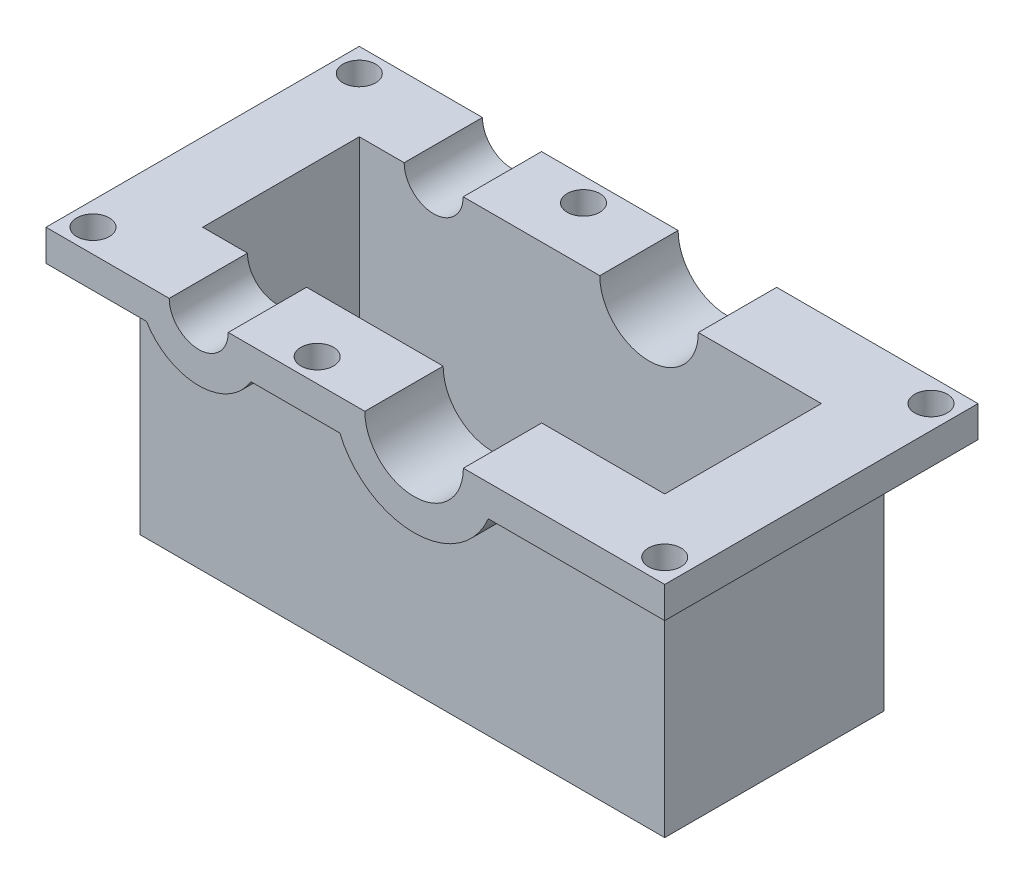
SolidWorks part; units mm, degrees
ref_plane "Front Plane" through (0, 0, 0) normal (0, 0, 1) x (1, 0, 0)
ref_plane "Top Plane" through (0, 0, 0) normal (0, 1, 0) x (1, 0, 0)
ref_plane "Right Plane" through (0, 0, 0) normal (1, 0, 0) x (0, 0, -1)
sketch "Sketch1" plane through (0, 0, 0) normal (0, 1, 0) x (1, 0, 0)
  line L1 (-21.2725, 8.89) -> (21.2725, 8.89)
  line L2 (-21.2725, 8.89) -> (-21.2725, -8.89)
  line L3 (-21.2725, -8.89) -> (21.2725, -8.89)
  line L4 (21.2725, 8.89) -> (21.2725, -8.89)
  line L5 (-21.2725, 8.89) -> (21.2725, -8.89) construction
  line L6 (-21.2725, -8.89) -> (21.2725, 8.89) construction
  point P0 (0, 0)
  dimension "D1" = 17.78
  dimension "D2" = 42.545
extrude "Boss-Extrude1" add sketch "Sketch1" along normal blind 2.54
sketch "Sketch2" plane through (0, 2.54, 0) normal (0, 1, 0) x (1, 0, 0)
  line L4 (21.2725, -8.89) -> (21.2725, 8.89)
  line L5 (21.2725, 8.89) -> (-21.2725, 8.89)
  line L6 (-21.2725, 8.89) -> (-21.2725, -8.89)
  line L7 (-21.2725, -8.89) -> (21.2725, -8.89)
  line L8 (21.2725, -8.89) -> (21.2725, 8.89)
  line L9 (21.2725, 8.89) -> (-21.2725, 8.89)
  line L10 (-21.2725, 8.89) -> (-21.2725, -8.89)
  line L11 (-21.2725, -8.89) -> (21.2725, -8.89)
  dimension "D1" = 0
extrude "Extrude-Thin1" add sketch "Sketch2" along normal blind 19.05 thin thin type one direction reverse wall 2.54
sketch "Sketch3" plane through (0, 21.59, 0) normal (0, 1, 0) x (1, 0, 0)
  line L1 (-25.0825, 12.7) -> (25.0825, 12.7)
  line L2 (-25.0825, 12.7) -> (-25.0825, -12.7)
  line L3 (-25.0825, -12.7) -> (25.0825, -12.7)
  line L4 (-21.2725, -8.89) -> (21.2725, -8.89)
  line L5 (21.2725, -8.89) -> (21.2725, 8.89)
  line L6 (21.2725, 8.89) -> (-21.2725, 8.89)
  line L7 (-21.2725, 8.89) -> (-21.2725, -8.89)
  line L8 (-21.2725, -8.89) -> (21.2725, -8.89)
  line L9 (21.2725, -8.89) -> (21.2725, 8.89)
  line L10 (21.2725, 8.89) -> (-21.2725, 8.89)
  line L11 (-21.2725, 8.89) -> (-21.2725, -8.89)
  line L12 (25.0825, 12.7) -> (25.0825, -12.7)
  line L13 (-25.0825, 12.7) -> (25.0825, -12.7) construction
  line L14 (-25.0825, -12.7) -> (25.0825, 12.7) construction
  point P2 (0, 0)
  dimension "D2" = 3.81
  dimension "D3" = 3.81
  dimension "D1" = 0
extrude "Boss-Extrude2" add sketch "Sketch3" against normal blind 2.54
sketch "Sketch4" plane through (0, 0, -12.7) normal (0, 0, -1) x (-1, 0, 0)
  line L0 (-25.0825, 21.59) -> (25.0825, 21.59) construction
  line L1 (-21.2725, 19.05) -> (-21.2725, 0) construction
  line L2 (21.2725, 19.05) -> (21.2725, 0) construction
  line L3 (-21.2725, 19.05) -> (-21.2725, 0) construction
  line L4 (21.2725, 19.05) -> (21.2725, 0) construction
  circle A0 centre (12.7, 21.59) radius 2.394
  circle A1 centre (-4.7625, 21.59) radius 3.9941
  dimension "D1" = 7.9883
  dimension "D2" = 4.7879
  dimension "D3" = 17.4625
  dimension "D4" = 16.51
extrude "Cut-Extrude1" cut sketch "Sketch4" against normal up to surface (25.4 mm away) up to face at (0, 20.32, 12.7)
sketch "Sketch5" plane through (0, 0, -8.89) normal (0, 0, -1) x (-1, 0, 0)
  line L0 (-25.0825, 19.05) -> (-7.845, 19.05) construction
  line L1 (-1.68, 19.05) -> (25.0825, 19.05) construction
  line L2 (-25.0825, 19.05) -> (-7.845, 19.05)
  line L3 (-1.68, 19.05) -> (25.0825, 19.05)
  line L6 (21.2725, 19.05) -> (-1.68, 19.05)
  line L8 (-7.845, 19.05) -> (-21.2725, 19.05)
  line L9 (-21.2725, 19.05) -> (-21.2725, 0)
  line L10 (-21.2725, 0) -> (21.2725, 0)
  line L11 (21.2725, 0) -> (21.2725, 19.05)
  line L12 (21.2725, 19.05) -> (-1.68, 19.05)
  line L14 (-7.845, 19.05) -> (-21.2725, 19.05)
  line L15 (-21.2725, 19.05) -> (-21.2725, 0)
  line L16 (-21.2725, 0) -> (21.2725, 0)
  line L17 (21.2725, 0) -> (21.2725, 19.05)
  circle A0 centre (12.7, 21.59) radius 4.9339
  circle A1 centre (-4.7625, 21.59) radius 6.5341
  arc A2 (10.306, 21.59) -> (15.094, 21.59) centre (12.7, 21.59) ccw construction
  arc A3 (-7.845, 19.05) -> (-1.68, 19.05) centre (-4.7625, 21.59) ccw
  arc A5 (-7.845, 19.05) -> (-1.68, 19.05) centre (-4.7625, 21.59) ccw
  arc A6 (10.306, 21.59) -> (15.094, 21.59) centre (12.7, 21.59) ccw
  dimension "D2" = 2.54
  dimension "D3" = 2.54
  dimension "D1" = 0
extrude "Boss-Extrude3" add sketch "Sketch5" along normal up to surface (3.81 mm away)
sketch "Sketch6" plane through (0, 0, 8.89) normal (0, 0, 1) x (1, 0, 0)
  line L6 (1.68, 19.05) -> (-21.2725, 19.05)
  line L8 (-21.2725, 19.05) -> (-21.2725, 0)
  line L9 (-21.2725, 0) -> (21.2725, 0)
  line L10 (21.2725, 0) -> (21.2725, 19.05)
  line L11 (21.2725, 19.05) -> (7.845, 19.05)
  line L12 (1.68, 19.05) -> (-21.2725, 19.05)
  line L14 (-21.2725, 19.05) -> (-21.2725, 0)
  line L15 (-21.2725, 0) -> (21.2725, 0)
  line L16 (21.2725, 0) -> (21.2725, 19.05)
  line L17 (21.2725, 19.05) -> (7.845, 19.05)
  circle A0 centre (-12.7, 21.59) radius 4.934
  circle A1 centre (4.7625, 21.59) radius 6.5341
  arc A2 (-15.094, 21.59) -> (-10.306, 21.59) centre (-12.7, 21.59) ccw construction
  arc A3 (1.68, 19.05) -> (7.845, 19.05) centre (4.7625, 21.59) ccw
  arc A5 (1.68, 19.05) -> (7.845, 19.05) centre (4.7625, 21.59) ccw
  arc A6 (-15.094, 21.59) -> (-10.306, 21.59) centre (-12.7, 21.59) ccw construction
  dimension "D2" = 2.54
  dimension "D3" = 2.54
  dimension "D1" = 0
extrude "Boss-Extrude4" add sketch "Sketch6" along normal up to surface (3.81 mm away)
sketch "Sketch7" plane through (0, 0, 0) normal (0, -1, 0) x (1, 0, 0)
  line L0 (0, 21.9043) -> (0, -22.0449) construction
  line L1 (-42.2616, 0) -> (46.2698, 0) construction
  line L2 (-36.1416, 10.795) -> (38.1659, 10.795) construction
  line L3 (23.1775, 10.2571) -> (23.1775, -23.0701) construction
  line L4 (21.2725, -12.7) -> (21.2725, 12.7)
  line L5 (21.2725, 12.7) -> (-21.2725, 12.7)
  line L6 (-21.2725, 12.7) -> (-21.2725, -12.7)
  line L7 (-21.2725, -12.7) -> (21.2725, -12.7)
  line L8 (37.1537, -10.795) -> (-37.1537, -10.795) construction
  line L9 (-23.1775, -10.2571) -> (-23.1775, 23.0701) construction
  line L10 (-10.306, 12.7) -> (0.7684, 12.7) construction
  line L11 (-25.0825, -12.7) -> (-25.0825, 12.7) construction
  line L12 (25.0825, 12.7) -> (25.0825, -12.7) construction
  line L13 (-21.2725, 8.89) -> (21.2725, 8.89) construction
  line L14 (-8.4701, 12.7) -> (-1.2578, 12.7) construction
  line L15 (21.2725, 8.89) -> (21.2725, -8.89) construction
  line L16 (21.2725, -8.89) -> (-21.2725, -8.89) construction
  line L17 (25.0825, -12.7) -> (10.7828, -12.7) construction
  line L18 (-10.306, 12.7) -> (0.7684, 12.7) construction
  line L19 (-21.2725, -8.89) -> (-21.2725, 8.89) construction
  line L20 (0.7684, 12.7) -> (0.7684, 8.89) construction
  line L21 (-10.306, 12.7) -> (-10.306, 8.89) construction
  circle A0 centre (-5.0003, 10.795) radius 1.3212
  circle A1 centre (-5.0003, -10.795) radius 1.3212
  circle A2 centre (23.1775, 10.795) radius 1.3212
  circle A3 centre (23.1775, -10.795) radius 1.3212
  circle A4 centre (-23.1775, 10.795) radius 1.3212
  circle A5 centre (-23.1775, -10.795) radius 1.3212
extrude "Cut-Extrude2" cut sketch "Sketch7" against normal through all contours A3 | A1 | A5 | A4 | A0 | A2
sketch "Sketch8" plane through (0, 19.05, 0) normal (0, -1, 0) x (1, 0, 0)
  line L0 (-25.0825, 10.795) -> (25.0825, 10.795) construction
  line L1 (-25.0825, -12.7) -> (-25.0825, 12.7) construction
  line L2 (25.0825, 12.7) -> (25.0825, -12.7) construction
  line L3 (23.1775, 12.7) -> (23.1775, -12.7) construction
  line L4 (21.2725, -8.89) -> (21.2725, 8.89)
  line L5 (21.2725, 8.89) -> (-21.2725, 8.89)
  line L6 (-21.2725, 8.89) -> (-21.2725, -8.89)
  line L7 (-21.2725, -8.89) -> (21.2725, -8.89)
  line L8 (21.2725, -8.89) -> (21.2725, 8.89)
  line L9 (21.2725, 8.89) -> (-21.2725, 8.89)
  line L10 (-21.2725, 8.89) -> (-21.2725, -8.89)
  line L11 (-21.2725, -8.89) -> (21.2725, -8.89)
  line L12 (10.7828, 12.7) -> (25.0825, 12.7) construction
  line L13 (25.0825, -12.7) -> (10.7828, -12.7) construction
  line L14 (25.0825, -10.795) -> (-25.0825, -10.795) construction
  line L15 (-23.1775, -12.7) -> (-23.1775, 12.7) construction
  line L16 (-16.9299, -12.7) -> (-25.0825, -12.7) construction
  line L17 (-25.0825, 12.7) -> (-16.9299, 12.7) construction
  line L18 (-8.4701, 12.7) -> (-16.9299, 12.7) construction
  line L19 (10.7828, 12.7) -> (-1.2578, 12.7) construction
  dimension "D1" = 0
equation "\"large_bearing_length\"= 0.25in"
equation "\"small_bearing_length\"= 0.25in"
equation "\"large_bearing_od\"= 0.3145in"
equation "\"small_bearing_od\"= 0.1885"
equation "\"large_gear_dp\"= 1.00in"
equation "\"small_gear_dp\" = 0.375in"
equation "\"shaft_spacing\"= ( \"large_gear_dp\" + \"small_gear_dp\" ) / 2"
equation "\"D2@Sketch3\"=\"large_bearing_length\"-0.1"
equation "\"D3@Sketch3\"=\"large_bearing_length\"-0.1"
equation "\"D1@Sketch4\"=\"large_bearing_od\""
equation "\"D2@Sketch4\"=\"small_bearing_od\""
equation "\"D3@Sketch4\"=\"shaft_spacing\""
equation "\"D4@Sketch4\"=(\"large_gear_dp\"+0.3)/2"
equation "\"D2@Sketch1\"=(\"large_gear_dp\"+\"small_gear_dp\")+0.3"
